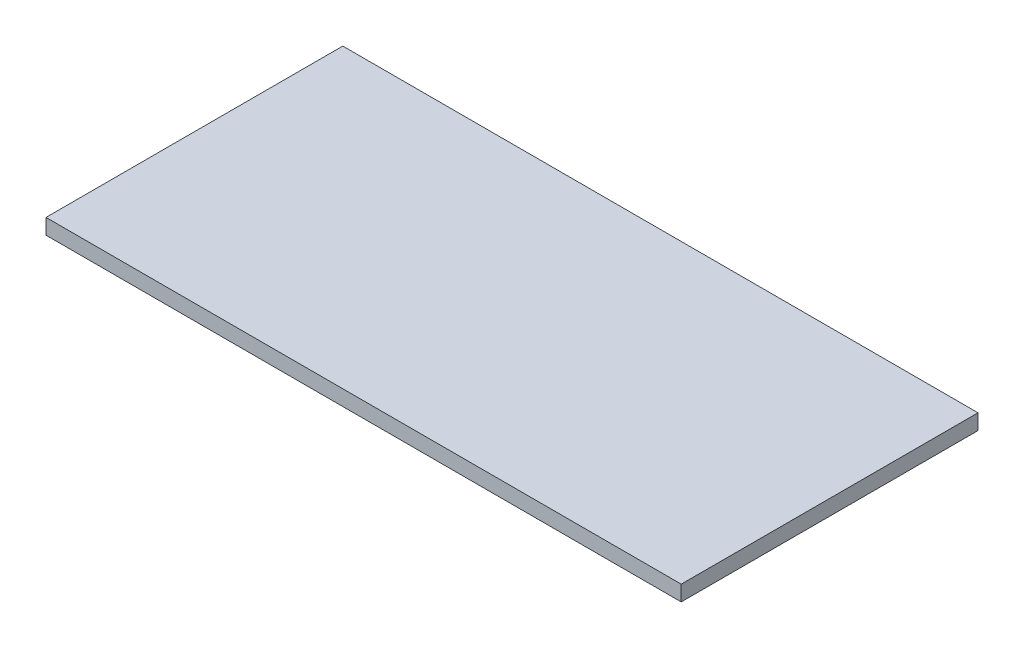
SolidWorks part; units mm, degrees
ref_plane "Front Plane" through (0, 0, 0) normal (0, 0, 1) x (1, 0, 0)
ref_plane "Top Plane" through (0, 0, 0) normal (0, 1, 0) x (1, 0, 0)
ref_plane "Right Plane" through (0, 0, 0) normal (1, 0, 0) x (0, 0, -1)
sketch "Sketch1" plane through (0, 0, 0) normal (0, 1, 0) x (1, 0, 0)
  line L0 (-20.6, 9.625) -> (20.6, -9.625) construction
  line L1 (-20.6, 9.625) -> (20.6, 9.625)
  line L2 (-20.6, 9.625) -> (-20.6, -9.625)
  line L3 (-20.6, -9.625) -> (20.6, -9.625)
  line L4 (20.6, 9.625) -> (20.6, -9.625)
  dimension "D1" = 41.2
  dimension "D2" = 19.25
extrude "Boss-Extrude1" add sketch "Sketch1" along normal blind 1
